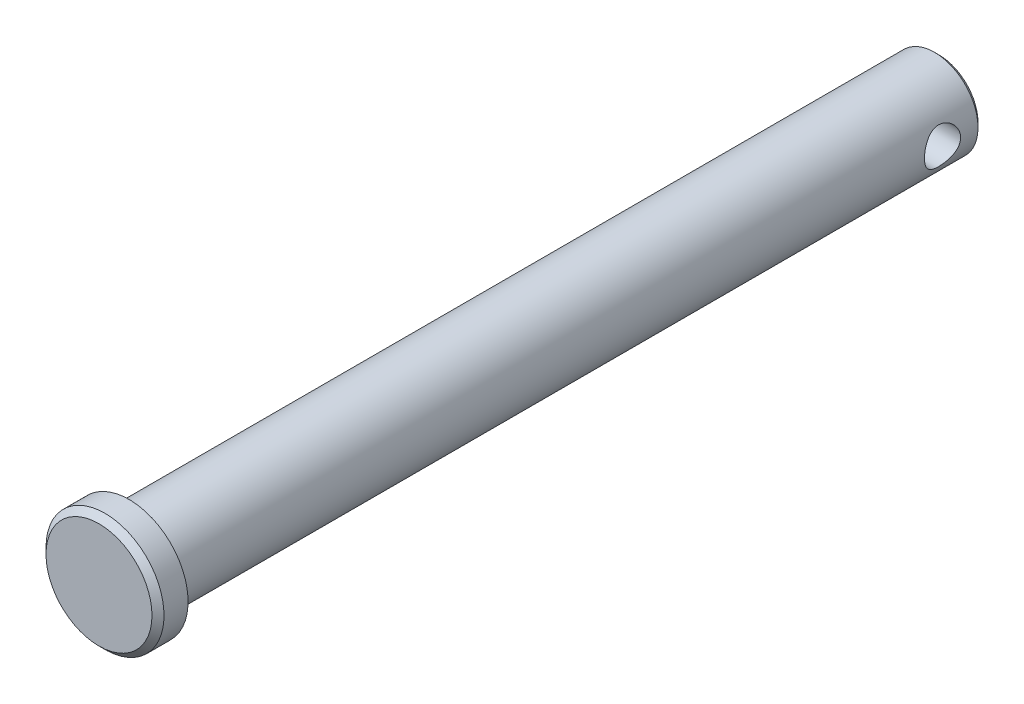
SolidWorks part; units mm, degrees
material "AISI 304"
ref_plane "Front" through (0, 0, 0) normal (0, 0, 1) x (1, 0, 0)
ref_plane "Top" through (0, 0, 0) normal (0, 1, 0) x (1, 0, 0)
ref_plane "Right" through (0, 0, 0) normal (1, 0, 0) x (0, 0, -1)
sketch "Sketch1" plane through (0, 0, 0) normal (0, 0, 1) x (1, 0, 0)
  circle A0 centre (0, 0) radius 4.7625
  point P3 (0, 4.7625)
  point P4 (0, -4.7625)
  dimension "dia" = 9.525
extrude "Extrude1" add sketch "Sketch1" along normal mid plane 88.9
sketch "Sketch2" plane through (0, 0, 44.45) normal (0, 0, 1) x (1, 0, 0)
  circle A0 centre (0, 0) radius 6.477
  dimension "head dia" = 12.954
extrude "Extrude2" add sketch "Sketch2" along normal blind 3.302
chamfer "Chamfer1" distance 0.6604 angle 45 1 edges at (6.477, 0, 47.752)
sketch "Sketch3" plane through (0, 0, 0) normal (1, 0, 0) x (0, 0, -1)
  line L0 (-44.45, -4.7625) -> (-44.45, 4.7625) construction
  circle A0 centre (40.0844, 0) radius 1.9844
  point P2 (38.1, 0)
  dimension "hole dia" = 3.9688
  dimension "useable Lg" = 82.55
extrude "Extrude3" cut sketch "Sketch3" against normal through all and the other way through all
chamfer "Chamfer2" distance 0.4763 angle 45 1 edges at (4.7625, 0, -44.45)
ref_plane "Plane1" through (0, 0, -40.0844) normal (0, 0, 1) x (1, 0, 0)
sketch "Sketch8" plane through (0, 0, 0) normal (1, 0, 0) x (0, 0, -1)
  line L0 (-47.752, 5.8166) -> (-47.752, -5.8166) construction
  line L1 (-47.0916, -6.477) -> (-44.45, -6.477) construction
  line L2 (44.45, -4.2863) -> (44.45, 4.2863) construction
  point P0 (-47.752, 6.477)
  point P1 (-44.45, 6.477)
  point P5 (44.45, 4.7625)
  point P8 (-47.752, -6.477)
  point P9 (44.45, -4.7625)
equation "\"D1@Chamfer1\" = \"head ht@Extrude2\" * .2"
equation "\"D1@Chamfer2\" = \"dia@Sketch1\" * .05"
